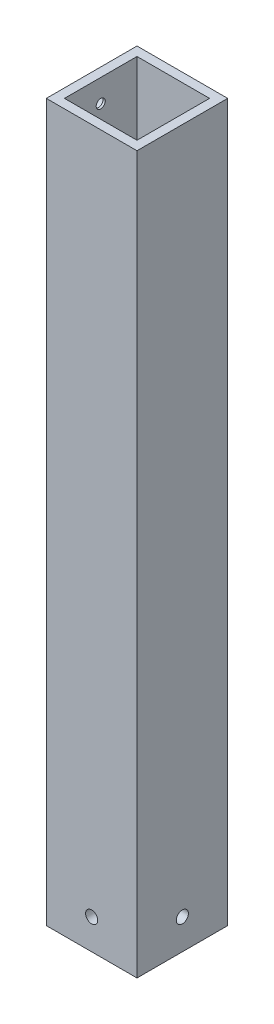
SolidWorks part; units mm, degrees
material "0.6010 (EN-GJL-100)"
ref_plane "Alzado" through (0, 0, 0) normal (0, 0, 1) x (1, 0, 0)
ref_plane "Planta" through (0, 0, 0) normal (0, 1, 0) x (1, 0, 0)
ref_plane "Vista lateral" through (0, 0, 0) normal (1, 0, 0) x (0, 0, -1)
sketch "Croquis1" plane through (0, 0, 0) normal (0, 1, 0) x (1, 0, 0)
  line L1 (15, -15) -> (-15, -15)
  line L2 (15, -15) -> (15, 15)
  line L3 (15, 15) -> (-15, 15)
  line L4 (-15, -15) -> (-15, 15)
  line L5 (15, -15) -> (-15, 15) construction
  line L6 (15, 15) -> (-15, -15) construction
  line L7 (13, -13) -> (-13, -13)
  line L8 (13, -13) -> (13, 13)
  line L9 (13, 13) -> (-13, 13)
  line L10 (-13, -13) -> (-13, 13)
  line L11 (13, -13) -> (-13, 13) construction
  line L12 (13, 13) -> (-13, -13) construction
  point P0 (0, 0)
  point P6 (0, 0)
  dimension "D1" = 30
  dimension "D2" = 30
  dimension "D3" = 2
  dimension "D4" = 2
extrude "Saliente-Extruir3" add sketch "Croquis1" along normal blind 230
sketch "Croquis2" plane through (0, 230, 0) normal (0, 1, 0) x (1, 0, 0)
  line L1 (-21.9189, 43.6684) -> (40.2161, 43.6684)
  line L2 (-21.9189, 43.6684) -> (-21.9189, -38.2609)
  line L3 (-21.9189, -38.2609) -> (40.2161, -38.2609)
  line L4 (40.2161, 43.6684) -> (40.2161, -38.2609)
extrude "Cortar-Extruir3" cut sketch "Croquis2" against normal blind 28
sketch "Croquis3" plane through (0, 0, 15) normal (0, 0, 1) x (1, 0, 0)
  line L0 (-15, 0) -> (15, 0) construction
  line L1 (-8, 42) -> (8, 42)
  line L2 (-8, 42) -> (-8, 2)
  line L3 (-8, 2) -> (8, 2)
  line L4 (8, 42) -> (8, 2)
  line L5 (-3, 11) -> (3, 11)
  line L6 (0, 42) -> (0, 28.1378)
  line L7 (-8, 22) -> (-1.2018, 22)
  line L8 (-15, 101) -> (-50.9144, 101)
  line L9 (-15, 202) -> (-15, 0) construction
  circle A1 centre (-3, 191) radius 2
  circle A3 centre (3, 169) radius 2
  circle A4 centre (3, 169) radius 2
  circle A5 centre (-3, 191) radius 2
  circle A6 centre (-3, 33) radius 2
  circle A7 centre (3, 11) radius 2
  dimension "D1" = 2
  dimension "D2" = 16
  dimension "D3" = 8
  dimension "D4" = 40
  dimension "D7" = 9
  dimension "D8" = 5
extrude "Cortar-Extruir9" cut sketch "Croquis3" against normal blind 15
sketch "Croquis4" plane through (0, 0, -15) normal (0, 0, -1) x (-1, 0, 0)
  line L0 (-15, 0) -> (15, 0) construction
  line L1 (-8, 42) -> (8, 42)
  line L2 (-8, 42) -> (-8, 2)
  line L3 (-8, 2) -> (8, 2)
  line L4 (8, 42) -> (8, 2)
  line L5 (-15, 202) -> (15, 202) construction
  line L6 (-8, 200) -> (8, 200)
  line L7 (-8, 200) -> (-8, 160)
  line L8 (-8, 160) -> (8, 160)
  line L10 (15, 202) -> (-15, 202) construction
  circle A0 centre (-3, 33) radius 2
  circle A1 centre (3, 11) radius 2
  circle A2 centre (-3, 191) radius 2
  circle A3 centre (3, 169) radius 2
  dimension "D5" = 5
  dimension "D7" = 9
  dimension "D1" = 2
  dimension "D2" = 40
  dimension "D3" = 16
  dimension "D4" = 8
  dimension "D6" = 9
  dimension "D8" = 5
  dimension "D9" = 16
  dimension "D10" = 2
  dimension "D11" = 40
extrude "Cortar-Extruir10" cut sketch "Croquis4" against normal blind 15 contours A2 | A3 | A1 | A0
sketch "Croquis5" plane through (0, 202, 0) normal (0, 1, 0) x (1, 0, 0)
  line L1 (-15, 15) -> (15, 15)
  line L2 (-15, 15) -> (-15, -15)
  line L3 (-15, -15) -> (15, -15)
  line L4 (15, 15) -> (15, -15)
  line L5 (13, -13) -> (-13, -13)
  line L6 (13, -13) -> (13, 13)
  line L7 (13, 13) -> (-13, 13)
  line L8 (-13, -13) -> (-13, 13)
sketch "Croquis6" plane through (0, 202, 0) normal (0, 1, 0) x (1, 0, 0)
extrude "Saliente-Extruir6" add sketch "Croquis5" along normal blind 12
sketch "Croquis7" plane through (0, 0, 15) normal (0, 0, 1) x (1, 0, 0)
  line L1 (-10.0145, 201.4665) -> (8.1054, 201.4665)
  line L2 (-10.0145, 201.4665) -> (-10.0145, 163.4469)
  line L3 (-10.0145, 163.4469) -> (8.1054, 163.4469)
  line L4 (8.1054, 201.4665) -> (8.1054, 163.4469)
extrude "Saliente-Extruir7" add sketch "Croquis7" against normal blind 2
sketch "Croquis8" plane through (0, 0, -15) normal (0, 0, -1) x (-1, 0, 0)
  line L1 (11.2248, 161.3456) -> (-8.0318, 161.3456)
  line L2 (11.2248, 161.3456) -> (11.2248, 196.4756)
  line L3 (11.2248, 196.4756) -> (-8.0318, 196.4756)
  line L4 (-8.0318, 161.3456) -> (-8.0318, 196.4756)
extrude "Saliente-Extruir8" add sketch "Croquis8" against normal blind 2
sketch "Croquis9" plane through (0, 0, 15) normal (0, 0, 1) x (1, 0, 0)
  line L0 (-15, 214) -> (15, 214) construction
  line L1 (-8, 212) -> (8, 212)
  line L2 (-8, 212) -> (-8, 172)
  line L3 (-8, 172) -> (8, 172)
  line L4 (8, 212) -> (8, 172)
  line L5 (0, 212) -> (0, 210.2737)
  line L6 (13, 214) -> (-13, 214) construction
  circle A0 centre (3, 181) radius 2
  circle A1 centre (-3, 203) radius 2
  point P8 (0, 214)
  dimension "D5" = 9
  dimension "D7" = 9
  dimension "D1" = 16
  dimension "D2" = 2
  dimension "D3" = 0
  dimension "D4" = 40
  dimension "D6" = 5
  dimension "D8" = 5
extrude "Cortar-Extruir11" cut sketch "Croquis9" against normal blind 2 contours A1 | A0
sketch "Croquis10" plane through (0, 0, -15) normal (0, 0, -1) x (-1, 0, 0)
  line L0 (-15, 214) -> (15, 214) construction
  line L1 (-8, 212) -> (8, 212)
  line L2 (-8, 212) -> (-8, 172)
  line L3 (-8, 172) -> (8, 172)
  line L4 (8, 212) -> (8, 172)
  line L5 (0, 212) -> (0, 209.0702)
  circle A0 centre (3, 181) radius 2
  circle A1 centre (-3, 203) radius 2
  point P8 (0, 214)
  dimension "D5" = 9
  dimension "D1" = 2
  dimension "D2" = 16
  dimension "D3" = 0
  dimension "D4" = 40
  dimension "D6" = 9
  dimension "D7" = 5
  dimension "D8" = 5
extrude "Cortar-Extruir12" cut sketch "Croquis10" against normal blind 2 contours A1 | A0
sketch "Croquis11" plane through (0, 214, 0) normal (0, 1, 0) x (1, 0, 0)
  line L1 (28.2549, -21.7184) -> (-40.5439, -21.7184)
  line L2 (28.2549, -21.7184) -> (28.2549, 21.2088)
  line L3 (28.2549, 21.2088) -> (-40.5439, 21.2088)
  line L4 (-40.5439, -21.7184) -> (-40.5439, 21.2088)
extrude "Cortar-Extruir14" cut sketch "Croquis11" against normal blind 2
sketch "Croquis12" plane through (0, 0, -15) normal (0, 0, -1) x (-1, 0, 0)
  circle A0 centre (3, 181) radius 2
  circle A1 centre (-3, 203) radius 2
extrude "Saliente-Extruir9" add sketch "Croquis12" against normal blind 2
sketch "Croquis13" plane through (0, 0, 15) normal (0, 0, 1) x (1, 0, 0)
  circle A0 centre (-3, 203) radius 2
  circle A1 centre (3, 181) radius 2
extrude "Saliente-Extruir10" add sketch "Croquis13" against normal blind 2
sketch "Croquis14" plane through (-15, 0, 0) normal (-1, 0, 0) x (0, 0, 1)
  line L0 (-15, 212) -> (15, 212) construction
  line L1 (-7.5, 224.5) -> (7.5, 224.5)
  line L2 (-7.5, 224.5) -> (-7.5, 199.5)
  line L3 (-7.5, 199.5) -> (7.5, 199.5)
  line L5 (-7.5, 224.5) -> (7.5, 199.5) construction
  line L6 (-7.5, 199.5) -> (7.5, 224.5) construction
  circle A0 centre (0, 204.5) radius 1.5
  point P0 (0, 212)
  dimension "D3" = 5
  dimension "D1" = 25
  dimension "D2" = 15
extrude "Cortar-Extruir18" cut sketch "Croquis14" against normal blind 20 contours A0
sketch "Croquis16" plane through (0, 212, 0) normal (0, 1, 0) x (1, 0, 0)
  line L1 (13, -13) -> (-13, -13)
  line L2 (13, -13) -> (13, 13)
  line L3 (13, 13) -> (-13, 13)
  line L4 (-13, -13) -> (-13, 13)
  line L5 (13, -13) -> (-13, 13) construction
  line L6 (13, 13) -> (-13, -13) construction
  line L7 (12, 12) -> (-12, 12)
  line L8 (12, 12) -> (12, -12)
  line L9 (12, -12) -> (-12, -12)
  line L10 (-12, 12) -> (-12, -12)
  line L11 (12, 12) -> (-12, -12) construction
  line L12 (12, -12) -> (-12, 12) construction
  point P0 (0, 0)
  point P7 (0, 0)
  dimension "D1" = 1
extrude "Saliente-Extruir11" add sketch "Croquis16" against normal blind 212
sketch "Croquis17" plane through (-13, 0, 0) normal (-1, 0, 0) x (0, 0, 1)
  circle A0 centre (0, 204.5) radius 1.5
extrude "Cortar-Extruir20" cut sketch "Croquis17" against normal blind 6
sketch "Croquis18" plane through (-15, 0, 0) normal (-1, 0, 0) x (0, 0, 1)
  circle A0 centre (0, 204.5) radius 2.5
extrude "Cortar-Extruir21" cut sketch "Croquis18" against normal blind 2.25
sketch "Croquis19" plane through (0, 0, 0) normal (0, -1, 0) x (1, 0, 0)
  line L1 (15, 15) -> (-15, 15)
  line L2 (15, 15) -> (15, -15)
  line L3 (15, -15) -> (-15, -15)
  line L4 (-15, 15) -> (-15, -15)
  line L5 (15, 15) -> (-15, -15) construction
  line L6 (15, -15) -> (-15, 15) construction
  line L7 (12, 12) -> (-12, 12)
  line L8 (12, 12) -> (12, -12)
  line L9 (12, -12) -> (-12, -12)
  line L10 (-12, 12) -> (-12, -12)
  line L11 (12, 12) -> (-12, -12) construction
  line L12 (12, -12) -> (-12, 12) construction
  point P0 (0, 0)
  point P7 (0, 0)
extrude "Saliente-Extruir12" add sketch "Croquis19" along normal blind 30
sketch "Croquis20" plane through (0, 0, 15) normal (0, 0, 1) x (1, 0, 0)
  circle A0 centre (3, 11) radius 2
  circle A1 centre (-3, 33) radius 2
extrude "Saliente-Extruir13" add sketch "Croquis20" against normal blind 2
sketch "Croquis21" plane through (0, 0, -15) normal (0, 0, -1) x (-1, 0, 0)
  circle A0 centre (3, 11) radius 2
  circle A1 centre (-3, 33) radius 2
extrude "Saliente-Extruir14" add sketch "Croquis21" against normal blind 2
sketch "Croquis22" plane through (-15, 0, 0) normal (-1, 0, 0) x (0, 0, 1)
  line L0 (15, -30) -> (-15, -30) construction
  circle A0 centre (0, -15) radius 2
  dimension "D1" = 15
extrude "Cortar-Extruir22" cut sketch "Croquis22" against normal blind 52
sketch "Croquis23" plane through (0, 0, -15) normal (0, 0, -1) x (-1, 0, 0)
  line L0 (15, -30) -> (-15, -30) construction
  circle A0 centre (0, -15) radius 2
  dimension "D1" = 15
extrude "Cortar-Extruir23" cut sketch "Croquis23" against normal blind 52
sketch "Croquis24" plane through (0, -30, 0) normal (0, -1, 0) x (-1, 0, 0)
  line L1 (-16.3083, -20.2379) -> (18.1898, -20.2379)
  line L2 (-16.3083, -20.2379) -> (-16.3083, 19.7535)
  line L3 (-16.3083, 19.7535) -> (18.1898, 19.7535)
  line L4 (18.1898, -20.2379) -> (18.1898, 19.7535)
extrude "Cortar-Extruir24" cut sketch "Croquis24" against normal blind 5
